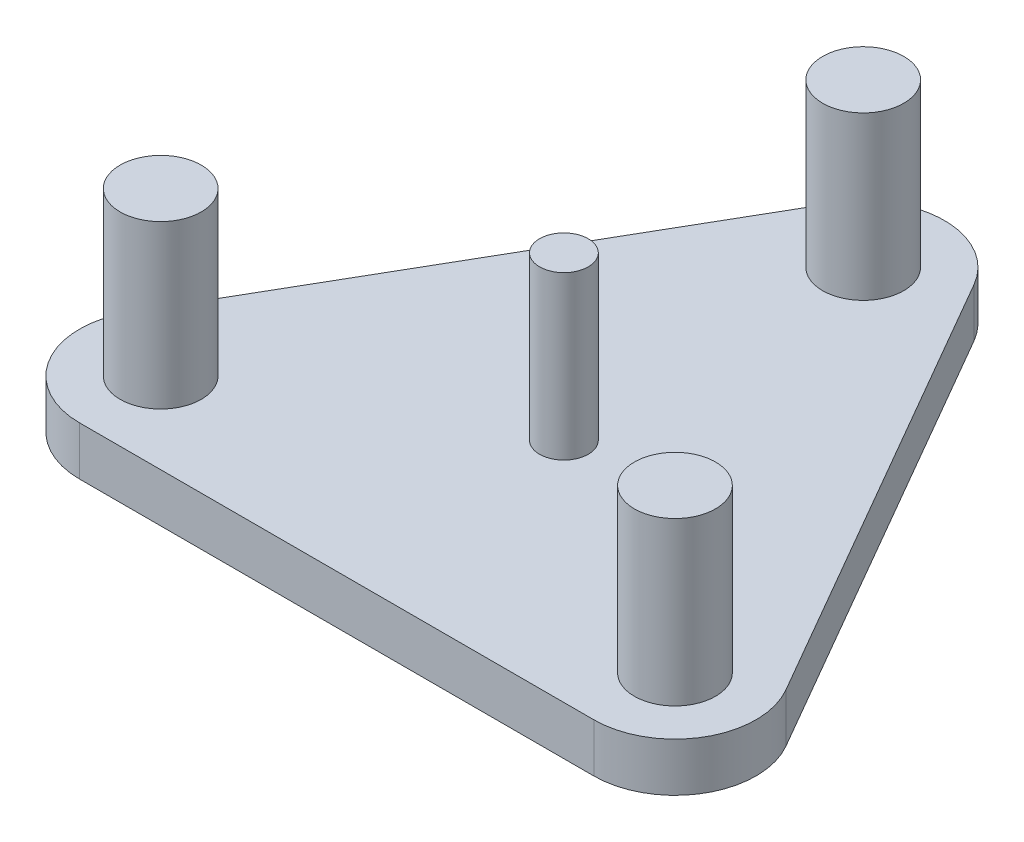
SolidWorks part; units mm, degrees
ref_plane "Alzado" through (0, 0, 0) normal (0, 0, 1) x (1, 0, 0)
ref_plane "Planta" through (0, 0, 0) normal (0, 1, 0) x (1, 0, 0)
ref_plane "Vista lateral" through (0, 0, 0) normal (1, 0, 0) x (0, 0, -1)
sketch "Croquis1" plane through (0, 0, 0) normal (0, 1, 0) x (1, 0, 0)
  line L0 (-15.8397, 0) -> (15.8397, 0)
  line L1 (20.1699, 7.5) -> (4.3301, 34.9352)
  line L2 (-4.3301, 34.9352) -> (-20.1699, 7.5)
  arc A0 (15.8397, 0) -> (20.1699, 7.5) centre (15.8397, 5) ccw
  arc A1 (-15.8397, 0) -> (-20.1699, 7.5) centre (-15.8397, 5) cw
  arc A2 (4.3301, 34.9352) -> (-4.3301, 34.9352) centre (0, 32.4352) ccw
  point P4 (0, 0)
  point P7 (24.5, 0)
  point P10 (-24.5, 0)
  point P13 (0, 42.4352)
  dimension "D4" = 5
  dimension "D1" = 49
  dimension "D2" = 49
  dimension "D3" = 49
extrude "Saliente-Extruir1" add sketch "Croquis1" along normal blind 3
sketch "Croquis2" plane through (0, 3, 0) normal (0, 1, 0) x (1, 0, 0)
  circle A0 centre (0, 32.4352) radius 2.5
  circle A1 centre (15.8397, 5) radius 2.5
  circle A2 centre (-15.8397, 5) radius 2.5
  dimension "D1" = 5
  dimension "D2" = 5
  dimension "D3" = 5
extrude "Saliente-Extruir2" add sketch "Croquis2" along normal blind 10
sketch "Croquis3" plane through (0, 3, 0) normal (0, 1, 0) x (1, 0, 0)
  line L0 (20.1699, 2.5) -> (-18.6228, 24.6083) construction
  line L3 (-20.1699, 2.5) -> (16.3747, 23.3104) construction
  arc A1 (-20.1699, 7.5) -> (-15.8397, 0) centre (-15.8397, 5) ccw construction
  arc A2 (15.8397, 0) -> (20.1699, 7.5) centre (15.8397, 5) ccw construction
  circle A3 centre (0.0081, 13.9904) radius 1.5
  dimension "D1" = 3
extrude "Saliente-Extruir3" add sketch "Croquis3" along normal blind 10
